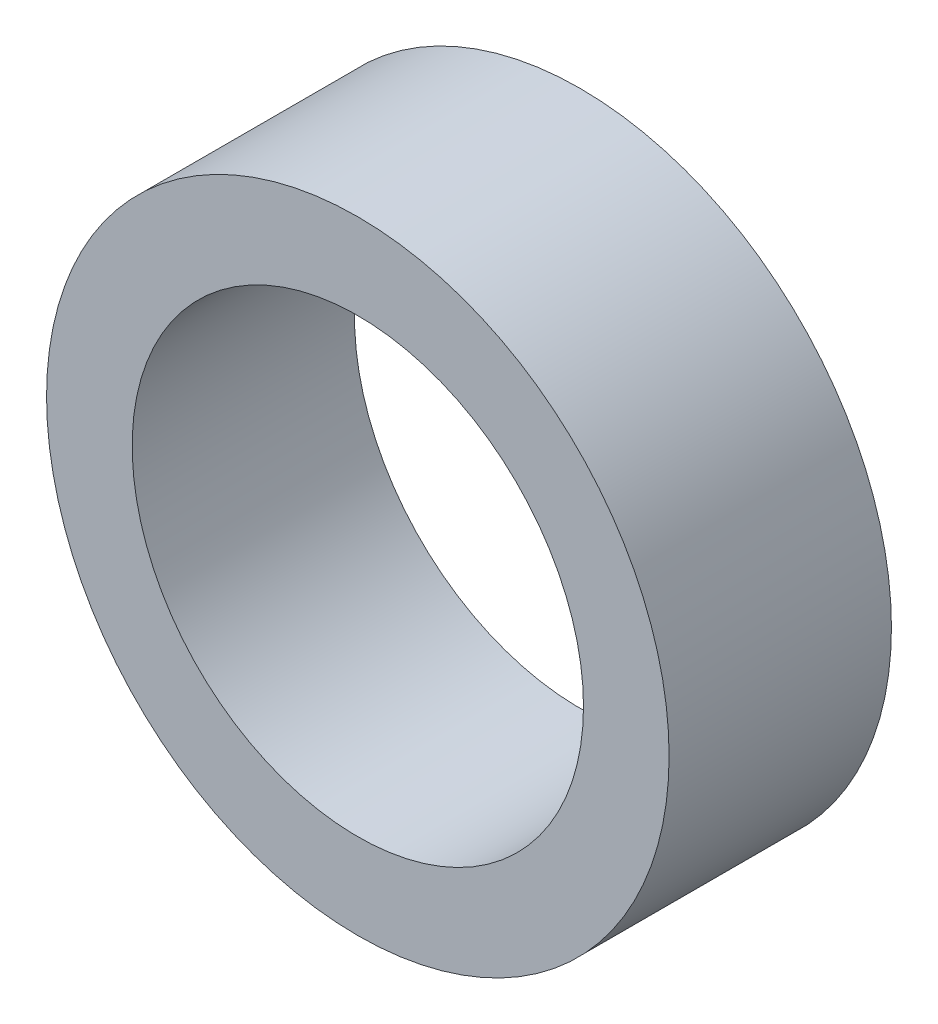
SolidWorks part; units mm, degrees
ref_plane "Front Plane" through (0, 0, 0) normal (0, 0, 1) x (1, 0, 0)
ref_plane "Top Plane" through (0, 0, 0) normal (0, 1, 0) x (1, 0, 0)
ref_plane "Right Plane" through (0, 0, 0) normal (1, 0, 0) x (0, 0, -1)
sketch "Sketch1" plane through (0, 0, 0) normal (0, 0, 1) x (1, 0, 0)
  circle A0 centre (0, 0) radius 5.075
  circle A1 centre (0, 0) radius 7
  dimension "D1" = 14
  dimension "D2" = 10.15
extrude "Boss-Extrude1" add sketch "Sketch1" along normal blind 5
